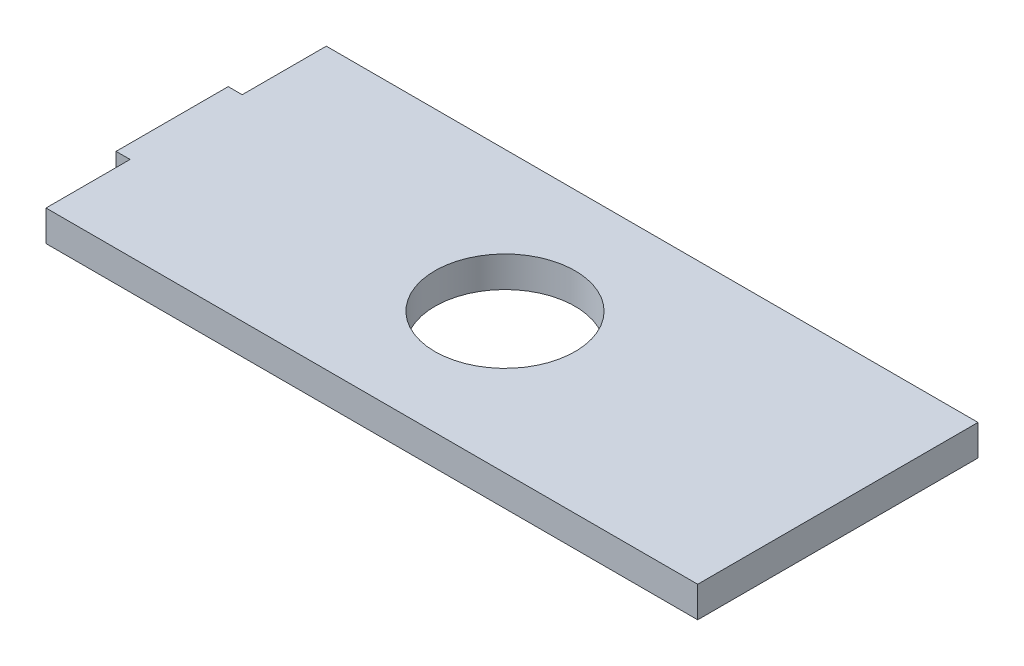
SolidWorks part; units mm, degrees
material "cardboard"
ref_plane "Front Plane" through (0, 0, 0) normal (0, 0, 1) x (1, 0, 0)
ref_plane "Top Plane" through (0, 0, 0) normal (0, 1, 0) x (1, 0, 0)
ref_plane "Right Plane" through (0, 0, 0) normal (1, 0, 0) x (0, 0, -1)
sketch "Sketch1" plane through (0, 0, 0) normal (0, 1, 0) x (1, 0, 0)
  line L0 (77.75, 11.5977) -> (70.8999, 7.6428)
  line L1 (103.25, -12.4023) -> (110.1001, -8.4474)
  line L2 (118.3999, 7.6428) -> (110.1001, 7.6428)
  line L3 (118.3999, -8.4474) -> (110.1001, -8.4474)
  line L4 (70.8999, 7.6428) -> (62.6001, 7.6428)
  line L5 (125.25, 11.5977) -> (118.3999, 7.6428)
  line L6 (125.25, -12.4023) -> (118.3999, -8.4474)
  line L7 (103.25, 11.5977) -> (110.1001, 7.6428)
  line L8 (125.25, 11.5977) -> (138, 11.5977)
  line L9 (125.25, -12.4023) -> (162, -12.4023)
  line L10 (55.75, 11.5977) -> (62.6001, 7.6428)
  line L11 (55.75, -12.4023) -> (62.6001, -8.4474)
  line L12 (77.75, -12.4023) -> (70.8999, -8.4474)
  line L13 (70.8999, -8.4474) -> (62.6001, -8.4474)
  line L14 (77.75, 11.5977) -> (103.25, 11.5977)
  line L15 (77.75, -12.4023) -> (103.25, -12.4023)
  line L16 (-12, 77.3477) -> (-8.0451, 70.4976)
  line L17 (12, 102.8477) -> (8.0451, 109.6979)
  line L18 (-8.0451, 117.9976) -> (-8.0451, 109.6979)
  line L19 (8.0451, 117.9976) -> (8.0451, 109.6979)
  line L20 (-8.0451, 70.4976) -> (-8.0451, 62.1979)
  line L21 (-12, 124.8477) -> (-8.0451, 117.9976)
  line L22 (12, 124.8477) -> (8.0451, 117.9976)
  line L23 (-12, 102.8477) -> (-8.0451, 109.6979)
  line L24 (-12, 124.8477) -> (-12, 137.5977)
  line L25 (12, 124.8477) -> (12, 161.5977)
  line L26 (-12, 55.3477) -> (-8.0451, 62.1979)
  line L27 (12, 55.3477) -> (8.0451, 62.1979)
  line L28 (12, 77.3477) -> (8.0451, 70.4976)
  line L29 (8.0451, 70.4976) -> (8.0451, 62.1979)
  line L30 (-12, 77.3477) -> (-12, 102.8477)
  line L31 (12, 77.3477) -> (12, 102.8477)
  line L32 (90.5, 36.5977) -> (90.5, 16.5977)
  line L33 (89.5, 36.5977) -> (89.5, 30.5977)
  line L34 (37, 11.5977) -> (43, 11.5977)
  line L35 (89.5, 30.5977) -> (91.5, 30.5977)
  line L36 (41.75, 11.5977) -> (41.75, 9.5977)
  line L37 (43, 11.5977) -> (55.75, 11.5977)
  line L38 (138, 11.5977) -> (138, -12.4023)
  line L39 (138, 11.5977) -> (162, 11.5977)
  line L40 (162, 11.5977) -> (162, 9.5977)
  line L41 (-28.4964, 13.952) -> (0, -14.5444)
  line L42 (-28.4964, 13.952) -> (-14.3543, 28.0941)
  line L43 (0, -14.5444) -> (14.1421, -0.4023)
  line L44 (-14.3543, 28.0941) -> (14.1421, -0.4023)
  line L45 (138, 11.5977) -> (138, 36.5977)
  line L46 (40, 36.5977) -> (162, 36.5977)
  line L47 (162, 36.5977) -> (162, 11.5977)
  line L48 (91.5, 30.5977) -> (91.5, 22.5977)
  line L49 (138, 36.5977) -> (138, 60.5977)
  line L50 (138, 60.5977) -> (147, 60.5977)
  line L51 (43, 36.5977) -> (43, 16.5977)
  line L52 (162, 60.5977) -> (162, 50.9197)
  line L53 (147, 60.5977) -> (147, 62.7977)
  line L54 (153, 62.7977) -> (153, 60.5977)
  line L55 (153, 60.5977) -> (162, 60.5977)
  line L56 (-59, 137.5977) -> (-59, 113.0977)
  line L57 (-39, 113.0977) -> (-39, 137.5977)
  line L58 (91.5, 22.5977) -> (89.5, 22.5977)
  line L59 (138, -12.4023) -> (138, -37.4023)
  line L60 (147, -37.4023) -> (153, -37.4023)
  line L61 (162, -37.4023) -> (162, -12.4023)
  line L62 (43, -37.4023) -> (43, -17.4023)
  line L63 (138, -37.4023) -> (138, -38.5823)
  line L64 (153, -38.5823) -> (162, -38.5823)
  line L65 (162, -38.5823) -> (162, -37.4023)
  line L66 (147, -38.5823) -> (147, -37.4023)
  line L67 (153, -38.5823) -> (153, -37.4023)
  line L68 (-38.18, -138.4023) -> (-38.18, -147.4023)
  line L69 (89.5, 22.5977) -> (89.5, 16.5977)
  line L70 (89.5, 11.5977) -> (89.5, 3.5977)
  line L71 (43, -12.4023) -> (55.75, -12.4023)
  line L72 (37, -12.4023) -> (43, -12.4023)
  line L73 (90.4738, 11.5977) -> (90.4738, -12.4023)
  line L74 (89.5, 3.5977) -> (91.5, 3.5977)
  line L75 (91.5, 3.5977) -> (91.5, -4.4023)
  line L76 (91.5, -4.4023) -> (89.5, -4.4023)
  line L77 (136, 11.5977) -> (136, 3.5977)
  line L78 (136, 3.5977) -> (140, 3.5977)
  line L79 (38.18, 161.5977) -> (38.18, 152.5977)
  line L80 (38, 34.5977) -> (38, 18.5977)
  line L81 (40, 16.5977) -> (138, 16.5977)
  line L82 (41.75, 23.5977) -> (41.75, 16.5977)
  line L83 (43, 29.5977) -> (40, 29.5977)
  line L84 (40, 29.5977) -> (40, 23.5977)
  line L85 (44.25, 5.5977) -> (41.75, 5.5977)
  line L86 (6, -42.1523) -> (6, -40.1523)
  line L87 (41.75, -6.4023) -> (44.25, -6.4023)
  line L88 (44.25, 5.5977) -> (44.25, -6.4023)
  line L89 (43, 11.5977) -> (43, 5.5977)
  line L90 (41.75, 9.5977) -> (44.25, 9.5977)
  line L91 (44.25, 9.5977) -> (44.25, 7.5977)
  line L92 (44.25, 7.5977) -> (41.75, 7.5977)
  line L93 (41.75, 7.5977) -> (41.75, 5.5977)
  line L94 (41.75, -8.4023) -> (41.75, -6.4023)
  line L95 (44.25, -8.4023) -> (41.75, -8.4023)
  line L96 (44.25, -10.4023) -> (44.25, -8.4023)
  line L97 (41.75, -10.4023) -> (44.25, -10.4023)
  line L98 (41.75, -12.4023) -> (41.75, -10.4023)
  line L99 (140, 3.5977) -> (140, -4.4023)
  line L100 (140, -4.4023) -> (136, -4.4023)
  line L101 (136, -4.4023) -> (136, -12.4023)
  line L102 (138, 13.5977) -> (146, 13.5977)
  line L103 (146, 13.5977) -> (146, 9.5977)
  line L104 (146, 9.5977) -> (154, 9.5977)
  line L105 (154, 9.5977) -> (154, 13.5977)
  line L106 (154, 13.5977) -> (162, 13.5977)
  line L107 (136.5, 36.5977) -> (136.5, 30.5977)
  line L108 (136.5, 30.5977) -> (139.5, 30.5977)
  line L109 (139.5, 30.5977) -> (139.5, 22.5977)
  line L110 (139.5, 22.5977) -> (136.5, 22.5977)
  line L111 (136.5, 22.5977) -> (136.5, 16.5977)
  line L112 (89.5, -4.4023) -> (89.5, -12.4023)
  line L113 (89.5, -23.4023) -> (89.5, -17.4023)
  line L114 (90.5, -37.4023) -> (90.5, -17.4023)
  line L115 (91.5, -23.4023) -> (89.5, -23.4023)
  line L116 (91.5, -31.4023) -> (91.5, -23.4023)
  line L117 (154, -14.4023) -> (162, -14.4023)
  line L118 (154, -10.4023) -> (154, -14.4023)
  line L119 (146, -10.4023) -> (154, -10.4023)
  line L120 (146, -14.4023) -> (146, -10.4023)
  line L121 (138, -14.4023) -> (146, -14.4023)
  line L122 (136.5, -23.4023) -> (136.5, -17.4023)
  line L123 (139.5, -23.4023) -> (136.5, -23.4023)
  line L124 (41.75, 36.5977) -> (41.75, 29.5977)
  line L125 (43, 23.5977) -> (40, 23.5977)
  line L126 (138, -37.4023) -> (40, -37.4023)
  line L127 (38, -35.4023) -> (38, -19.4023)
  line L128 (40, -17.4023) -> (138, -17.4023)
  line L129 (139.5, -31.4023) -> (139.5, -23.4023)
  line L130 (136.5, -31.4023) -> (139.5, -31.4023)
  line L131 (136.5, -37.4023) -> (136.5, -31.4023)
  line L132 (89.5, -31.4023) -> (91.5, -31.4023)
  line L133 (89.5, -37.4023) -> (89.5, -31.4023)
  line L134 (138, 38.5977) -> (146, 38.5977)
  line L135 (146, 38.5977) -> (146, 34.5977)
  line L136 (146, 34.5977) -> (154, 34.5977)
  line L137 (154, 34.5977) -> (154, 38.5977)
  line L138 (154, 38.5977) -> (162, 38.5977)
  line L139 (-44.5, 133.3477) -> (-44.5, 117.3477)
  line L140 (-56, 133.3477) -> (-53.5, 133.3477)
  line L141 (-56, 133.3477) -> (-56, 117.3477)
  line L142 (-56, 117.3477) -> (-53.5, 117.3477)
  line L143 (-53.5, 133.3477) -> (-53.5, 117.3477)
  line L144 (41.75, -24.4023) -> (41.75, -17.4023)
  line L145 (43, -24.4023) -> (40, -24.4023)
  line L146 (40, -30.4023) -> (40, -24.4023)
  line L147 (43, -30.4023) -> (40, -30.4023)
  line L148 (41.75, -37.4023) -> (41.75, -30.4023)
  line L149 (197, 4.5977) -> (197, -5.4023)
  line L150 (192, 9.5977) -> (162, 9.5977)
  line L151 (192, -10.4023) -> (162, -10.4023)
  line L152 (192, 9.5977) -> (197, 4.5977)
  line L153 (197, -5.4023) -> (192, -10.4023)
  line L154 (162, -10.4023) -> (162, -12.4023)
  line L155 (138, 62.7977) -> (147, 62.7977)
  line L156 (138, 62.7977) -> (138, 64.7977)
  line L157 (138, 64.7977) -> (162, 64.7977)
  line L158 (162, 64.7977) -> (162, 62.7977)
  line L159 (153, 62.7977) -> (162, 62.7977)
  line L160 (-42, 117.3477) -> (-44.5, 117.3477)
  line L161 (-42, 133.3477) -> (-42, 117.3477)
  line L162 (-42, 133.3477) -> (-44.5, 133.3477)
  line L163 (155.4, 50.9197) -> (162, 50.9197)
  line L164 (155.4, 50.9197) -> (155.4, 46.4197)
  line L165 (155.4, 46.4197) -> (162, 46.4197)
  line L166 (162, 46.4197) -> (162, 36.5977)
  line L167 (12, -78.1523) -> (8.0451, -71.3021)
  line L168 (-12, -103.6523) -> (-8.0451, -110.5024)
  line L169 (8.0451, -118.8021) -> (8.0451, -110.5024)
  line L170 (12, -37.4023) -> (12, -43.4023)
  line L171 (12, -42.1523) -> (10, -42.1523)
  line L172 (12, -43.4023) -> (12, -56.1523)
  line L173 (-8.0451, -118.8021) -> (-8.0451, -110.5024)
  line L174 (8.0451, -71.3021) -> (8.0451, -63.0024)
  line L175 (12, -125.6523) -> (8.0451, -118.8021)
  line L176 (-12, -125.6523) -> (-8.0451, -118.8021)
  line L177 (12, -103.6523) -> (8.0451, -110.5024)
  line L178 (12, -125.6523) -> (12, -138.4023)
  line L179 (-12, -125.6523) -> (-12, -162.4023)
  line L180 (12, -56.1523) -> (8.0451, -63.0024)
  line L181 (-12, -56.1523) -> (-8.0451, -63.0024)
  line L182 (37, -43.4023) -> (17, -43.4023)
  line L183 (-12, -78.1523) -> (-8.0451, -71.3021)
  line L184 (-8.0451, -71.3021) -> (-8.0451, -63.0024)
  line L185 (12, -78.1523) -> (12, -103.6523)
  line L186 (-12, -78.1523) -> (-12, -103.6523)
  line L187 (37, -90.9023) -> (17, -90.9023)
  line L188 (37, -89.9023) -> (31, -89.9023)
  line L189 (31, -89.9023) -> (31, -91.9023)
  line L190 (12, -138.4023) -> (-12, -138.4023)
  line L191 (12, -138.4023) -> (12, -162.4023)
  line L192 (12, -162.4023) -> (10, -162.4023)
  line L193 (12, -138.4023) -> (37, -138.4023)
  line L194 (37, -40.4023) -> (37, -162.4023)
  line L195 (-37, -43.4023) -> (-17, -43.4023)
  line L196 (37, -162.4023) -> (12, -162.4023)
  line L197 (31, -91.9023) -> (23, -91.9023)
  line L198 (37, -138.4023) -> (61, -138.4023)
  line L199 (61, -138.4023) -> (61, -147.4023)
  line L200 (61, -162.4023) -> (51.322, -162.4023)
  line L201 (61, -147.4023) -> (63.2, -147.4023)
  line L202 (63.2, -153.4023) -> (61, -153.4023)
  line L203 (61, -153.4023) -> (61, -162.4023)
  line L204 (-12, -43.4023) -> (-12, -56.1523)
  line L205 (-12, -37.4023) -> (-12, -43.4023)
  line L206 (23, -91.9023) -> (23, -89.9023)
  line L207 (-12, -138.4023) -> (-37, -138.4023)
  line L208 (-37, -147.4023) -> (-37, -153.4023)
  line L209 (38.18, 146.5977) -> (38.18, 137.5977)
  line L210 (35, -38.4023) -> (19, -38.4023)
  line L211 (17, -40.4023) -> (17, -138.4023)
  line L212 (24, -42.1523) -> (17, -42.1523)
  line L213 (30, -43.4023) -> (30, -40.4023)
  line L214 (30, -40.4023) -> (24, -40.4023)
  line L215 (6, -44.6523) -> (6, -42.1523)
  line L216 (-37, -162.4023) -> (-12, -162.4023)
  line L217 (-6, -42.1523) -> (-6, -44.6523)
  line L218 (6, -44.6523) -> (-6, -44.6523)
  line L219 (12, -43.4023) -> (6, -43.4023)
  line L220 (10, -42.1523) -> (10, -44.6523)
  line L221 (10, -44.6523) -> (8, -44.6523)
  line L222 (8, -44.6523) -> (8, -42.1523)
  line L223 (8, -42.1523) -> (6, -42.1523)
  line L224 (-8, -42.1523) -> (-6, -42.1523)
  line L225 (-8, -44.6523) -> (-8, -42.1523)
  line L226 (-10, -44.6523) -> (-8, -44.6523)
  line L227 (-10, -42.1523) -> (-10, -44.6523)
  line L228 (-12, -42.1523) -> (-10, -42.1523)
  line L229 (-37, -138.4023) -> (-38.18, -138.4023)
  line L230 (-38.18, -153.4023) -> (-38.18, -162.4023)
  line L231 (-38.18, -162.4023) -> (-37, -162.4023)
  line L232 (-38.18, -147.4023) -> (-37, -147.4023)
  line L233 (-38.18, -153.4023) -> (-37, -153.4023)
  line L234 (-162, 37.7777) -> (-153, 37.7777)
  line L235 (23, -89.9023) -> (17, -89.9023)
  line L236 (12, -89.9023) -> (4, -89.9023)
  line L237 (12, -90.8761) -> (-12, -90.8761)
  line L238 (4, -89.9023) -> (4, -91.9023)
  line L239 (4, -91.9023) -> (-4, -91.9023)
  line L240 (-4, -91.9023) -> (-4, -89.9023)
  line L241 (12, -136.4023) -> (4, -136.4023)
  line L242 (4, -136.4023) -> (4, -140.4023)
  line L243 (4, -140.4023) -> (-4, -140.4023)
  line L244 (-4, -140.4023) -> (-4, -136.4023)
  line L245 (-4, -136.4023) -> (-12, -136.4023)
  line L246 (14, -138.4023) -> (14, -146.4023)
  line L247 (14, -146.4023) -> (10, -146.4023)
  line L248 (10, -146.4023) -> (10, -154.4023)
  line L249 (10, -154.4023) -> (14, -154.4023)
  line L250 (14, -154.4023) -> (14, -162.4023)
  line L251 (37, -136.9023) -> (31, -136.9023)
  line L252 (31, -136.9023) -> (31, -139.9023)
  line L253 (31, -139.9023) -> (23, -139.9023)
  line L254 (37, -42.1523) -> (30, -42.1523)
  line L255 (24, -43.4023) -> (24, -40.4023)
  line L256 (-37, -138.4023) -> (-37, -40.4023)
  line L257 (-35, -38.4023) -> (-19, -38.4023)
  line L258 (-17, -40.4023) -> (-17, -138.4023)
  line L259 (23, -139.9023) -> (23, -136.9023)
  line L260 (23, -136.9023) -> (17, -136.9023)
  line L261 (-4, -89.9023) -> (-12, -89.9023)
  line L262 (-23, -89.9023) -> (-17, -89.9023)
  line L263 (-37, -90.9023) -> (-17, -90.9023)
  line L264 (-23, -91.9023) -> (-23, -89.9023)
  line L265 (-31, -91.9023) -> (-23, -91.9023)
  line L266 (-14, -154.4023) -> (-14, -162.4023)
  line L267 (-10, -154.4023) -> (-14, -154.4023)
  line L268 (-10, -146.4023) -> (-10, -154.4023)
  line L269 (-14, -146.4023) -> (-10, -146.4023)
  line L270 (-14, -138.4023) -> (-14, -146.4023)
  line L271 (-23, -136.9023) -> (-17, -136.9023)
  line L272 (-23, -139.9023) -> (-23, -136.9023)
  line L273 (-31, -139.9023) -> (-23, -139.9023)
  line L274 (-24, -42.1523) -> (-17, -42.1523)
  line L275 (-24, -43.4023) -> (-24, -40.4023)
  line L276 (-30, -40.4023) -> (-24, -40.4023)
  line L277 (-30, -43.4023) -> (-30, -40.4023)
  line L278 (-37, -42.1523) -> (-30, -42.1523)
  line L279 (-31, -136.9023) -> (-31, -139.9023)
  line L280 (-37, -136.9023) -> (-31, -136.9023)
  line L281 (-31, -89.9023) -> (-31, -91.9023)
  line L282 (-37, -89.9023) -> (-31, -89.9023)
  line L283 (39, -138.4023) -> (39, -146.4023)
  line L284 (39, -146.4023) -> (35, -146.4023)
  line L285 (35, -146.4023) -> (35, -154.4023)
  line L286 (35, -154.4023) -> (39, -154.4023)
  line L287 (39, -154.4023) -> (39, -162.4023)
  line L288 (5, -197.4023) -> (-5, -197.4023)
  line L289 (10, -192.4023) -> (10, -162.4023)
  line L290 (-10, -192.4023) -> (-10, -162.4023)
  line L291 (10, -192.4023) -> (5, -197.4023)
  line L292 (-5, -197.4023) -> (-10, -192.4023)
  line L293 (-10, -162.4023) -> (-12, -162.4023)
  line L294 (63.2, -138.4023) -> (63.2, -147.4023)
  line L295 (63.2, -138.4023) -> (65.2, -138.4023)
  line L296 (65.2, -138.4023) -> (65.2, -162.4023)
  line L297 (65.2, -162.4023) -> (63.2, -162.4023)
  line L298 (63.2, -153.4023) -> (63.2, -162.4023)
  line L299 (-37, -12.4023) -> (-43, -12.4023)
  line L300 (-41.75, -12.4023) -> (-41.75, -10.4023)
  line L301 (-43, -12.4023) -> (-55.75, -12.4023)
  line L302 (51.322, -155.8023) -> (51.322, -162.4023)
  line L303 (51.322, -155.8023) -> (46.822, -155.8023)
  line L304 (-43, -37.4023) -> (-43, -17.4023)
  line L305 (46.822, -155.8023) -> (46.822, -162.4023)
  line L306 (46.822, -162.4023) -> (37, -162.4023)
  line L307 (-77.75, -12.4023) -> (-70.8999, -8.4474)
  line L308 (-103.25, 11.5977) -> (-110.1001, 7.6428)
  line L309 (-118.3999, -8.4474) -> (-110.1001, -8.4474)
  line L310 (-118.3999, 7.6428) -> (-110.1001, 7.6428)
  line L311 (-70.8999, -8.4474) -> (-62.6001, -8.4474)
  line L312 (-125.25, -12.4023) -> (-118.3999, -8.4474)
  line L313 (-125.25, 11.5977) -> (-118.3999, 7.6428)
  line L314 (-103.25, -12.4023) -> (-110.1001, -8.4474)
  line L315 (-125.25, -12.4023) -> (-138, -12.4023)
  line L316 (-43, 36.5977) -> (-43, 16.5977)
  line L317 (-125.25, 11.5977) -> (-162, 11.5977)
  line L318 (-55.75, -12.4023) -> (-62.6001, -8.4474)
  line L319 (-55.75, 11.5977) -> (-62.6001, 7.6428)
  line L320 (-77.75, 11.5977) -> (-70.8999, 7.6428)
  line L321 (-70.8999, 7.6428) -> (-62.6001, 7.6428)
  line L322 (-77.75, -12.4023) -> (-103.25, -12.4023)
  line L323 (-77.75, 11.5977) -> (-103.25, 11.5977)
  line L324 (-90.5, -37.4023) -> (-90.5, -17.4023)
  line L325 (-43, 11.5977) -> (-55.75, 11.5977)
  line L326 (-37, 11.5977) -> (-43, 11.5977)
  line L327 (-89.5, -37.4023) -> (-89.5, -31.4023)
  line L328 (-89.5, -31.4023) -> (-91.5, -31.4023)
  line L329 (-138, -12.4023) -> (-138, 11.5977)
  line L330 (-138, -12.4023) -> (-162, -12.4023)
  line L331 (-162, -12.4023) -> (-162, -10.4023)
  line L332 (-138, -12.4023) -> (-138, -37.4023)
  line L333 (138, -38.5823) -> (147, -38.5823)
  line L334 (-38, -35.4023) -> (-38, -19.4023)
  line L335 (-40, -17.4023) -> (-138, -17.4023)
  line L336 (-41.75, -24.4023) -> (-41.75, -17.4023)
  line L337 (-43, -30.4023) -> (-40, -30.4023)
  line L338 (-40, -30.4023) -> (-40, -24.4023)
  line L339 (-44.25, -6.4023) -> (-41.75, -6.4023)
  line L340 (-40, -37.4023) -> (-162, -37.4023)
  line L341 (-41.75, 5.5977) -> (-44.25, 5.5977)
  line L342 (-44.25, -6.4023) -> (-44.25, 5.5977)
  line L343 (-43, -12.4023) -> (-43, -6.4023)
  line L344 (-41.75, -10.4023) -> (-44.25, -10.4023)
  line L345 (-44.25, -10.4023) -> (-44.25, -8.4023)
  line L346 (-44.25, -8.4023) -> (-41.75, -8.4023)
  line L347 (-41.75, -8.4023) -> (-41.75, -6.4023)
  line L348 (-41.75, 7.5977) -> (-41.75, 5.5977)
  line L349 (-44.25, 7.5977) -> (-41.75, 7.5977)
  line L350 (-44.25, 9.5977) -> (-44.25, 7.5977)
  line L351 (-41.75, 9.5977) -> (-44.25, 9.5977)
  line L352 (-41.75, 11.5977) -> (-41.75, 9.5977)
  line L353 (-162, -37.4023) -> (-162, -12.4023)
  line L354 (-91.5, -31.4023) -> (-91.5, -23.4023)
  line L355 (-138, -37.4023) -> (-138, -61.4023)
  line L356 (-138, -61.4023) -> (-147, -61.4023)
  line L357 (-162, -61.4023) -> (-162, -51.7243)
  line L358 (-147, -61.4023) -> (-147, -63.6023)
  line L359 (-153, -63.6023) -> (-153, -61.4023)
  line L360 (-153, -61.4023) -> (-162, -61.4023)
  line L361 (-91.5, -23.4023) -> (-89.5, -23.4023)
  line L362 (-138, 11.5977) -> (-138, 36.5977)
  line L363 (-147, 36.5977) -> (-153, 36.5977)
  line L364 (-162, 36.5977) -> (-162, 11.5977)
  line L365 (-138, 36.5977) -> (-138, 37.7777)
  line L366 (-162, 37.7777) -> (-162, 36.5977)
  line L367 (-147, 37.7777) -> (-147, 36.5977)
  line L368 (-153, 37.7777) -> (-153, 36.5977)
  line L369 (-147, 37.7777) -> (-138, 37.7777)
  line L370 (-89.5, -23.4023) -> (-89.5, -17.4023)
  line L371 (-89.5, -12.4023) -> (-89.5, -4.4023)
  line L372 (-90.4738, -12.4023) -> (-90.4738, 11.5977)
  line L373 (-89.5, -4.4023) -> (-91.5, -4.4023)
  line L374 (-41.75, -37.4023) -> (-41.75, -30.4023)
  line L375 (-43, -24.4023) -> (-40, -24.4023)
  line L376 (-138, 36.5977) -> (-40, 36.5977)
  line L377 (-38, 34.5977) -> (-38, 18.5977)
  line L378 (-40, 16.5977) -> (-138, 16.5977)
  line L379 (-91.5, -4.4023) -> (-91.5, 3.5977)
  line L380 (-91.5, 3.5977) -> (-89.5, 3.5977)
  line L381 (-136, -12.4023) -> (-136, -4.4023)
  line L382 (-136, -4.4023) -> (-140, -4.4023)
  line L383 (-140, -4.4023) -> (-140, 3.5977)
  line L384 (-140, 3.5977) -> (-136, 3.5977)
  line L385 (-136, 3.5977) -> (-136, 11.5977)
  line L386 (-138, -14.4023) -> (-146, -14.4023)
  line L387 (-146, -14.4023) -> (-146, -10.4023)
  line L388 (-146, -10.4023) -> (-154, -10.4023)
  line L389 (-154, -10.4023) -> (-154, -14.4023)
  line L390 (-154, -14.4023) -> (-162, -14.4023)
  line L391 (-136.5, -37.4023) -> (-136.5, -31.4023)
  line L392 (-37, 90.0977) -> (-17, 90.0977)
  line L393 (-37, 89.0977) -> (-31, 89.0977)
  line L394 (-41.75, 23.5977) -> (-41.75, 16.5977)
  line L395 (-43, 23.5977) -> (-40, 23.5977)
  line L396 (-40, 29.5977) -> (-40, 23.5977)
  line L397 (-43, 29.5977) -> (-40, 29.5977)
  line L398 (-41.75, 36.5977) -> (-41.75, 29.5977)
  line L399 (-136.5, -31.4023) -> (-139.5, -31.4023)
  line L400 (-139.5, -31.4023) -> (-139.5, -23.4023)
  line L401 (-139.5, -23.4023) -> (-136.5, -23.4023)
  line L402 (-136.5, -23.4023) -> (-136.5, -17.4023)
  line L403 (-89.5, 3.5977) -> (-89.5, 11.5977)
  line L404 (-89.5, 22.5977) -> (-89.5, 16.5977)
  line L405 (-90.5, 36.5977) -> (-90.5, 16.5977)
  line L406 (-91.5, 22.5977) -> (-89.5, 22.5977)
  line L407 (-91.5, 30.5977) -> (-91.5, 22.5977)
  line L408 (-154, 13.5977) -> (-162, 13.5977)
  line L409 (-154, 9.5977) -> (-154, 13.5977)
  line L410 (-146, 9.5977) -> (-154, 9.5977)
  line L411 (-146, 13.5977) -> (-146, 9.5977)
  line L412 (-138, 13.5977) -> (-146, 13.5977)
  line L413 (-136.5, 22.5977) -> (-136.5, 16.5977)
  line L414 (-139.5, 22.5977) -> (-136.5, 22.5977)
  line L415 (-139.5, 30.5977) -> (-139.5, 22.5977)
  line L416 (-136.5, 30.5977) -> (-139.5, 30.5977)
  line L417 (-136.5, 36.5977) -> (-136.5, 30.5977)
  line L418 (-89.5, 30.5977) -> (-91.5, 30.5977)
  line L419 (-89.5, 36.5977) -> (-89.5, 30.5977)
  line L420 (-138, -39.4023) -> (-146, -39.4023)
  line L421 (-146, -39.4023) -> (-146, -35.4023)
  line L422 (-146, -35.4023) -> (-154, -35.4023)
  line L423 (-154, -35.4023) -> (-154, -39.4023)
  line L424 (-154, -39.4023) -> (-162, -39.4023)
  line L425 (-12, 41.3477) -> (-10, 41.3477)
  line L426 (-31, 89.0977) -> (-31, 91.0977)
  line L427 (-12, 137.5977) -> (12, 137.5977)
  line L428 (-12, 137.5977) -> (-12, 161.5977)
  line L429 (-12, 161.5977) -> (-10, 161.5977)
  line L430 (-12, 137.5977) -> (-37, 137.5977)
  line L431 (-37, 137.5977) -> (-37, 161.5977)
  line L432 (-37, 161.5977) -> (-12, 161.5977)
  line L433 (-37, 137.5977) -> (-37, 42.5977)
  line L434 (-37, 42.5977) -> (-17, 42.5977)
  line L435 (-17, 42.5977) -> (-17, 137.5977)
  line L436 (-31, 91.0977) -> (-23, 91.0977)
  line L437 (-37, 137.5977) -> (-61, 137.5977)
  line L438 (-61, 137.5977) -> (-61, 146.5977)
  line L439 (-61, 161.5977) -> (-51.322, 161.5977)
  line L440 (-61, 146.5977) -> (-63.2, 146.5977)
  line L441 (-63.2, 152.5977) -> (-61, 152.5977)
  line L442 (-61, 152.5977) -> (-61, 161.5977)
  line L443 (-59, 113.0977) -> (-39, 113.0977)
  line L444 (37, 42.5977) -> (17, 42.5977)
  line L445 (-23, 91.0977) -> (-23, 89.0977)
  line L446 (37, 137.5977) -> (37, 42.5977)
  line L447 (17, 42.5977) -> (17, 137.5977)
  line L448 (12, 137.5977) -> (37, 137.5977)
  line L449 (37, 146.5977) -> (37, 152.5977)
  line L450 (37, 161.5977) -> (12, 161.5977)
  line L451 (12, 36.5977) -> (12, 55.3477)
  line L452 (37, 137.5977) -> (38.18, 137.5977)
  line L453 (38.18, 161.5977) -> (37, 161.5977)
  line L454 (38.18, 146.5977) -> (37, 146.5977)
  line L455 (38.18, 152.5977) -> (37, 152.5977)
  line L456 (-37, 42.5977) -> (-37, 39.5977)
  line L457 (-35, 37.5977) -> (-19, 37.5977)
  line L458 (-17, 39.5977) -> (-17, 42.5977)
  line L459 (35, 37.5977) -> (19, 37.5977)
  line L460 (17, 39.5977) -> (17, 42.5977)
  line L461 (-6, 43.8477) -> (-6, 41.3477)
  line L462 (-23, 89.0977) -> (-17, 89.0977)
  line L463 (6, 41.3477) -> (6, 43.8477)
  line L464 (-6, 43.8477) -> (6, 43.8477)
  line L465 (-12, 42.5977) -> (-6, 42.5977)
  line L466 (-10, 41.3477) -> (-10, 43.8477)
  line L467 (-10, 43.8477) -> (-8, 43.8477)
  line L468 (-8, 43.8477) -> (-8, 41.3477)
  line L469 (-8, 41.3477) -> (-6, 41.3477)
  line L470 (8, 41.3477) -> (6, 41.3477)
  line L471 (8, 43.8477) -> (8, 41.3477)
  line L472 (10, 43.8477) -> (8, 43.8477)
  line L473 (10, 41.3477) -> (10, 43.8477)
  line L474 (12, 41.3477) -> (10, 41.3477)
  line L475 (-12, 89.0977) -> (-4, 89.0977)
  line L476 (-12, 90.0715) -> (12, 90.0715)
  line L477 (-4, 89.0977) -> (-4, 91.0977)
  line L478 (-4, 91.0977) -> (4, 91.0977)
  line L479 (4, 91.0977) -> (4, 89.0977)
  line L480 (-12, 135.5977) -> (-4, 135.5977)
  line L481 (-4, 135.5977) -> (-4, 139.5977)
  line L482 (-4, 139.5977) -> (4, 139.5977)
  line L483 (4, 139.5977) -> (4, 135.5977)
  line L484 (4, 135.5977) -> (12, 135.5977)
  line L485 (-14, 137.5977) -> (-14, 145.5977)
  line L486 (-14, 145.5977) -> (-10, 145.5977)
  line L487 (-10, 145.5977) -> (-10, 153.5977)
  line L488 (-10, 153.5977) -> (-14, 153.5977)
  line L489 (-14, 153.5977) -> (-14, 161.5977)
  line L490 (-37, 136.0977) -> (-31, 136.0977)
  line L491 (-31, 136.0977) -> (-31, 139.0977)
  line L492 (-31, 139.0977) -> (-23, 139.0977)
  line L493 (-23, 139.0977) -> (-23, 136.0977)
  line L494 (-23, 136.0977) -> (-17, 136.0977)
  line L495 (4, 89.0977) -> (12, 89.0977)
  line L496 (23, 89.0977) -> (17, 89.0977)
  line L497 (37, 90.0977) -> (17, 90.0977)
  line L498 (23, 91.0977) -> (23, 89.0977)
  line L499 (31, 91.0977) -> (23, 91.0977)
  line L500 (-37, 41.3477) -> (-30, 41.3477)
  line L501 (30, 39.5977) -> (24, 39.5977)
  line L502 (24, 41.3477) -> (17, 41.3477)
  line L503 (-30, 42.5977) -> (-30, 39.5977)
  line L504 (-24, 41.3477) -> (-17, 41.3477)
  line L505 (14, 153.5977) -> (14, 161.5977)
  line L506 (10, 153.5977) -> (14, 153.5977)
  line L507 (10, 145.5977) -> (10, 153.5977)
  line L508 (14, 145.5977) -> (10, 145.5977)
  line L509 (14, 137.5977) -> (14, 145.5977)
  line L510 (23, 136.0977) -> (17, 136.0977)
  line L511 (23, 139.0977) -> (23, 136.0977)
  line L512 (31, 139.0977) -> (23, 139.0977)
  line L513 (31, 136.0977) -> (31, 139.0977)
  line L514 (37, 136.0977) -> (31, 136.0977)
  line L515 (31, 89.0977) -> (31, 91.0977)
  line L516 (37, 89.0977) -> (31, 89.0977)
  line L517 (12, 36.5977) -> (20.9645, 27.6332)
  line L518 (37, -12.4023) -> (28.0355, -21.3668)
  line L519 (-12, -37.4023) -> (-20.9645, -28.4378)
  line L520 (24, 42.5977) -> (24, 39.5977)
  line L521 (-24, 42.5977) -> (-24, 39.5977)
  line L522 (30, 42.5977) -> (30, 39.5977)
  line L523 (37, 41.3477) -> (30, 41.3477)
  line L524 (-39, 137.5977) -> (-39, 145.5977)
  line L525 (-39, 145.5977) -> (-35, 145.5977)
  line L526 (-35, 145.5977) -> (-35, 153.5977)
  line L527 (-35, 153.5977) -> (-39, 153.5977)
  line L528 (-39, 153.5977) -> (-39, 161.5977)
  line L529 (-59, 136.0977) -> (-52, 136.0977)
  line L530 (-52, 136.0977) -> (-52, 139.0977)
  line L531 (-52, 139.0977) -> (-46, 139.0977)
  line L532 (-46, 139.0977) -> (-46, 136.0977)
  line L533 (-46, 136.0977) -> (-39, 136.0977)
  line L534 (-12, 36.5977) -> (-12, 55.3477)
  line L535 (43, -6.4023) -> (43, -12.4023)
  line L536 (6, 42.5977) -> (12, 42.5977)
  line L537 (-43, 5.5977) -> (-43, 11.5977)
  line L538 (-6, -43.4023) -> (-12, -43.4023)
  line L539 (-5, 196.5977) -> (5, 196.5977)
  line L540 (-10, 191.5977) -> (-10, 161.5977)
  line L541 (10, 191.5977) -> (10, 161.5977)
  line L542 (-10, 191.5977) -> (-5, 196.5977)
  line L543 (5, 196.5977) -> (10, 191.5977)
  line L544 (133.75, 55.5977) -> (117.75, 55.5977)
  line L545 (133.75, 55.5977) -> (133.75, 53.0977)
  line L546 (-197, -5.4023) -> (-197, 4.5977)
  line L547 (-192, -10.4023) -> (-162, -10.4023)
  line L548 (-192, 9.5977) -> (-162, 9.5977)
  line L549 (-192, -10.4023) -> (-197, -5.4023)
  line L550 (-197, 4.5977) -> (-192, 9.5977)
  line L551 (-162, 9.5977) -> (-162, 11.5977)
  line L552 (-138, -63.6023) -> (-147, -63.6023)
  line L553 (-138, -63.6023) -> (-138, -65.6023)
  line L554 (-138, -65.6023) -> (-162, -65.6023)
  line L555 (-162, -65.6023) -> (-162, -63.6023)
  line L556 (10, 161.5977) -> (12, 161.5977)
  line L557 (-153, -63.6023) -> (-162, -63.6023)
  line L558 (133.75, 53.0977) -> (117.75, 53.0977)
  line L559 (117.75, 55.5977) -> (117.75, 53.0977)
  line L560 (133.75, 44.0977) -> (117.75, 44.0977)
  line L561 (133.75, 41.5977) -> (133.75, 44.0977)
  line L562 (133.75, 41.5977) -> (117.75, 41.5977)
  line L563 (117.75, 41.5977) -> (117.75, 44.0977)
  line L564 (136.5, 58.5977) -> (136.5, 51.5977)
  line L565 (136.5, 51.5977) -> (139.5, 51.5977)
  line L566 (-155.4, -51.7243) -> (-162, -51.7243)
  line L567 (-155.4, -51.7243) -> (-155.4, -47.2243)
  line L568 (-155.4, -47.2243) -> (-162, -47.2243)
  line L569 (-63.2, 137.5977) -> (-63.2, 146.5977)
  line L570 (-63.2, 137.5977) -> (-65.2, 137.5977)
  line L571 (-65.2, 137.5977) -> (-65.2, 161.5977)
  line L572 (-65.2, 161.5977) -> (-63.2, 161.5977)
  line L573 (-63.2, 152.5977) -> (-63.2, 161.5977)
  line L574 (-162, -47.2243) -> (-162, -37.4023)
  line L575 (139.5, 51.5977) -> (139.5, 45.5977)
  line L576 (-46.3621, 123.4425) -> (-47.5, 123.4425)
  line L577 (-51.6379, 127.4838) -> (-50.5, 127.4838)
  line L578 (-51.6379, 127.4838) -> (-51.6379, 123.4425)
  line L579 (-51.6379, 123.4425) -> (-50.5, 123.4425)
  line L580 (-50.5, 127.4838) -> (-50.5, 123.4425)
  line L581 (-47.5, 127.4838) -> (-47.5, 123.4425)
  line L582 (-46.3621, 127.4838) -> (-47.5, 127.4838)
  line L583 (-46.3621, 127.4838) -> (-46.3621, 123.4425)
  line L584 (139.5, 45.5977) -> (136.5, 45.5977)
  line L585 (136.5, 45.5977) -> (136.5, 38.5977)
  line L586 (113.5, 38.5977) -> (138, 38.5977)
  line L587 (113.5, 58.5977) -> (113.5, 38.5977)
  line L588 (138, 58.5977) -> (113.5, 58.5977)
  line L589 (56, -134.1523) -> (56, -118.1523)
  line L590 (56, -134.1523) -> (53.5, -134.1523)
  line L591 (-51.322, 154.9977) -> (-51.322, 161.5977)
  line L592 (-51.322, 154.9977) -> (-46.822, 154.9977)
  line L593 (-46.822, 154.9977) -> (-46.822, 161.5977)
  line L594 (-46.822, 161.5977) -> (-37, 161.5977)
  line L595 (53.5, -134.1523) -> (53.5, -118.1523)
  line L596 (56, -118.1523) -> (53.5, -118.1523)
  line L597 (-13.8934, 34.7043) -> (-12, 36.5977)
  line L598 (-20.9645, 34.7043) -> (-23.0858, 36.8256)
  line L599 (-35.1066, 20.5622) -> (-37.2279, 22.6835)
  line L600 (-37.2279, 22.6835) -> (-23.0858, 36.8256)
  line L601 (6, -40.1523) -> (-6, -40.1523)
  line L602 (41.75, 5.5977) -> (39.75, 5.5977)
  line L603 (-6, -42.1523) -> (-6, -40.1523)
  line L604 (41.75, -6.4023) -> (39.75, -6.4023)
  line L605 (39.75, 5.5977) -> (39.75, -6.4023)
  line L606 (-41.75, -6.4023) -> (-39.75, -6.4023)
  line L607 (-39.75, -6.4023) -> (-39.75, 5.5977)
  line L608 (-41.75, 5.5977) -> (-39.75, 5.5977)
  line L609 (-6, 41.3477) -> (-6, 39.3477)
  line L610 (-6, 39.3477) -> (6, 39.3477)
  line L611 (6, 41.3477) -> (6, 39.3477)
  line L612 (-37, 11.5977) -> (-35.1066, 13.4911)
  line L613 (-30, 39.5977) -> (-24, 39.5977)
  line L614 (25.9142, -19.2454) -> (18.8431, -26.3165)
  line L615 (18.8431, 25.5119) -> (25.9142, 18.4409)
  line L616 (25.9142, 18.4409) -> (28.0355, 20.5622)
  line L617 (44.5, -134.1523) -> (44.5, -118.1523)
  line L618 (42, -134.1523) -> (44.5, -134.1523)
  line L619 (42, -134.1523) -> (42, -118.1523)
  line L620 (42, -118.1523) -> (44.5, -118.1523)
  line L621 (59, -136.9023) -> (52, -136.9023)
  line L622 (52, -136.9023) -> (52, -139.9023)
  line L623 (52, -139.9023) -> (46, -139.9023)
  line L624 (46, -139.9023) -> (46, -136.9023)
  line L625 (46, -136.9023) -> (39, -136.9023)
  line L626 (39, -113.9023) -> (39, -138.4023)
  line L627 (59, -113.9023) -> (39, -113.9023)
  line L628 (59, -138.4023) -> (59, -113.9023)
  line L629 (-133.75, -56.4023) -> (-117.75, -56.4023)
  line L630 (-133.75, -56.4023) -> (-133.75, -53.9023)
  line L631 (-133.75, -53.9023) -> (-117.75, -53.9023)
  line L632 (-117.75, -56.4023) -> (-117.75, -53.9023)
  line L633 (-133.75, -44.9023) -> (-117.75, -44.9023)
  line L634 (-133.75, -42.4023) -> (-133.75, -44.9023)
  line L635 (-133.75, -42.4023) -> (-117.75, -42.4023)
  line L636 (-117.75, -42.4023) -> (-117.75, -44.9023)
  line L637 (-136.5, -59.4023) -> (-136.5, -52.4023)
  line L638 (-136.5, -52.4023) -> (-139.5, -52.4023)
  line L639 (-139.5, -52.4023) -> (-139.5, -46.4023)
  line L640 (-139.5, -46.4023) -> (-136.5, -46.4023)
  line L641 (-136.5, -46.4023) -> (-136.5, -39.4023)
  line L642 (-113.5, -39.4023) -> (-138, -39.4023)
  line L643 (-113.5, -59.4023) -> (-113.5, -39.4023)
  line L644 (-138, -59.4023) -> (-113.5, -59.4023)
  line L645 (127.8861, 51.2356) -> (123.8448, 51.2356)
  line L646 (127.8861, 51.2356) -> (127.8861, 50.0977)
  line L647 (127.8861, 50.0977) -> (123.8448, 50.0977)
  line L648 (123.8448, 51.2356) -> (123.8448, 50.0977)
  line L649 (127.8861, 47.0977) -> (123.8448, 47.0977)
  line L650 (18.8431, 25.5119) -> (20.9645, 27.6332)
  line L651 (127.8861, 45.9598) -> (127.8861, 47.0977)
  line L652 (127.8861, 45.9598) -> (123.8448, 45.9598)
  line L653 (123.8448, 45.9598) -> (123.8448, 47.0977)
  line L654 (51.6379, -128.2884) -> (51.6379, -124.2471)
  line L655 (51.6379, -128.2884) -> (50.5, -128.2884)
  line L656 (50.5, -128.2884) -> (50.5, -124.2471)
  line L657 (51.6379, -124.2471) -> (50.5, -124.2471)
  line L658 (47.5, -128.2884) -> (47.5, -124.2471)
  line L659 (46.3621, -128.2884) -> (47.5, -128.2884)
  line L660 (46.3621, -128.2884) -> (46.3621, -124.2471)
  line L661 (46.3621, -124.2471) -> (47.5, -124.2471)
  line L662 (-127.8861, -52.0402) -> (-123.8448, -52.0402)
  line L663 (-127.8861, -52.0402) -> (-127.8861, -50.9023)
  line L664 (-127.8861, -50.9023) -> (-123.8448, -50.9023)
  line L665 (-123.8448, -52.0402) -> (-123.8448, -50.9023)
  line L666 (-127.8861, -47.9023) -> (-123.8448, -47.9023)
  line L667 (-127.8861, -46.7644) -> (-127.8861, -47.9023)
  line L668 (-127.8861, -46.7644) -> (-123.8448, -46.7644)
  line L669 (-123.8448, -46.7644) -> (-123.8448, -47.9023)
  line L670 (28.0355, 20.5622) -> (37, 11.5977)
  line L671 (18.8431, -26.3165) -> (20.9645, -28.4378)
  line L672 (25.9142, -19.2454) -> (28.0355, -21.3668)
  line L673 (-18.8431, -26.3165) -> (-25.9142, -19.2454)
  line L674 (-25.9142, -19.2454) -> (-28.0355, -21.3668)
  line L675 (-18.8431, -26.3165) -> (-20.9645, -28.4378)
  line L676 (20.9645, -28.4378) -> (12, -37.4023)
  line L677 (-28.0355, -21.3668) -> (-37, -12.4023)
  line L678 (37, 42.5977) -> (37, 39.5977)
  circle A0 centre (156.7175, 41.8802) radius 1.5
  circle A1 centre (143.2825, 55.3152) radius 1.5
  circle A2 centre (155.6569, 54.2546) radius 1.5
  circle A3 centre (144.3431, 42.9409) radius 1.5
  circle A4 centre (150, 48.5977) radius 3.1
  circle A5 centre (150, 24.0977) radius 5
  circle A6 centre (150, -24.9023) radius 5
  circle A7 centre (66.75, 26.5977) radius 5
  circle A8 centre (114.0006, 26.5977) radius 5
  circle A9 centre (66.75, -27.4023) radius 5
  circle A10 centre (114.0006, -27.4023) radius 5
  circle A11 centre (150, -0.4023) radius 7
  circle A12 centre (42.2825, -157.1198) radius 1.5
  circle A13 centre (55.7175, -143.6848) radius 1.5
  circle A14 centre (54.6569, -156.0591) radius 1.5
  circle A15 centre (43.3431, -144.7454) radius 1.5
  circle A16 centre (49, -150.4023) radius 3.1
  circle A17 centre (24.5, -150.4023) radius 5
  circle A18 centre (-42.2825, 156.3152) radius 1.5
  circle A19 centre (-55.7175, 142.8802) radius 1.5
  circle A20 centre (-54.6569, 155.2546) radius 1.5
  circle A21 centre (-43.3431, 143.9409) radius 1.5
  circle A22 centre (-49, 149.5977) radius 3.1
  circle A23 centre (-24.5, -150.4023) radius 5
  circle A24 centre (27, -67.1523) radius 5
  circle A25 centre (27, -114.4029) radius 5
  circle A26 centre (-27, -67.1523) radius 5
  circle A27 centre (-27, -114.4029) radius 5
  circle A28 centre (0, -150.4023) radius 7
  circle A29 centre (-156.7175, -42.6848) radius 1.5
  circle A30 centre (-24.5, 149.5977) radius 5
  circle A31 centre (24.5, 149.5977) radius 5
  circle A32 centre (-143.2825, -56.1198) radius 1.5
  circle A33 centre (-155.6569, -55.0591) radius 1.5
  circle A34 centre (-144.3431, -43.7454) radius 1.5
  circle A35 centre (-150, -49.4023) radius 3.1
  circle A36 centre (-150, -24.9023) radius 5
  circle A37 centre (-150, 24.0977) radius 5
  circle A38 centre (-66.75, -27.4023) radius 5
  circle A39 centre (-114.0006, -27.4023) radius 5
  circle A40 centre (-66.75, 26.5977) radius 5
  circle A41 centre (-114.0006, 26.5977) radius 5
  circle A42 centre (-150, -0.4023) radius 7
  circle A43 centre (-27, 66.3477) radius 5
  circle A44 centre (-27, 113.5983) radius 5
  circle A45 centre (27, 66.3477) radius 5
  circle A46 centre (27, 113.5983) radius 5
  arc A47 (40, 36.5977) -> (38, 34.5977) centre (40, 34.5977) ccw
  arc A48 (38, 18.5977) -> (40, 16.5977) centre (40, 18.5977) ccw
  arc A49 (-19, 37.5977) -> (-17, 39.5977) centre (-19, 39.5977) ccw
  arc A50 (-37, 39.5977) -> (-35, 37.5977) centre (-35, 39.5977) ccw
  arc A51 (37, 39.5977) -> (35, 37.5977) centre (35, 39.5977) cw
  arc A52 (19, 37.5977) -> (17, 39.5977) centre (19, 39.5977) cw
  arc A53 (40, -37.4023) -> (38, -35.4023) centre (40, -35.4023) cw
  arc A54 (38, -19.4023) -> (40, -17.4023) centre (40, -19.4023) cw
  arc A55 (37, -40.4023) -> (35, -38.4023) centre (35, -40.4023) ccw
  arc A56 (19, -38.4023) -> (17, -40.4023) centre (19, -40.4023) ccw
  arc A57 (-37, -40.4023) -> (-35, -38.4023) centre (-35, -40.4023) cw
  arc A58 (-19, -38.4023) -> (-17, -40.4023) centre (-19, -40.4023) cw
  arc A59 (-40, -37.4023) -> (-38, -35.4023) centre (-40, -35.4023) ccw
  arc A60 (-38, -19.4023) -> (-40, -17.4023) centre (-40, -19.4023) ccw
  arc A61 (-40, 36.5977) -> (-38, 34.5977) centre (-40, 34.5977) cw
  arc A62 (-38, 18.5977) -> (-40, 16.5977) centre (-40, 18.5977) cw
  arc A63 (-13.8934, 34.7043) -> (-20.9645, 34.7043) centre (-17.4289, 38.2398) cw
  arc A64 (-35.1066, 20.5622) -> (-35.1066, 13.4911) centre (-38.6421, 17.0266) cw
  circle A65 centre (0, 149.5977) radius 7
  point P194 (0, -0.4023)
  point P589 (0, -0.4023)
  point P595 (0, -0.4023)
  point P596 (0, -0.4023)
  point P601 (0, -0.4023)
  point P604 (0, -0.4023)
  point P629 (0, -0.4023)
  point P660 (0, -0.4023)
  point P686 (0, -0.4023)
  point P715 (0, -0.4023)
  point P716 (0, -0.4023)
  point P740 (0, -0.4023)
  point P743 (0, -0.4023)
  point P783 (0, -0.4023)
  point P809 (0, -0.4023)
  point P816 (0, -0.4023)
  point P829 (0, -0.4023)
  point P860 (0, -0.4023)
  point P885 (0, -0.4023)
  point P890 (0, -0.4023)
  point P910 (0, -0.4023)
extrude "Boss-Extrude1" add sketch "Sketch1" along normal blind 2.2 contours L376 L419 L418 L405 L406 L404 L378 L316 A40
